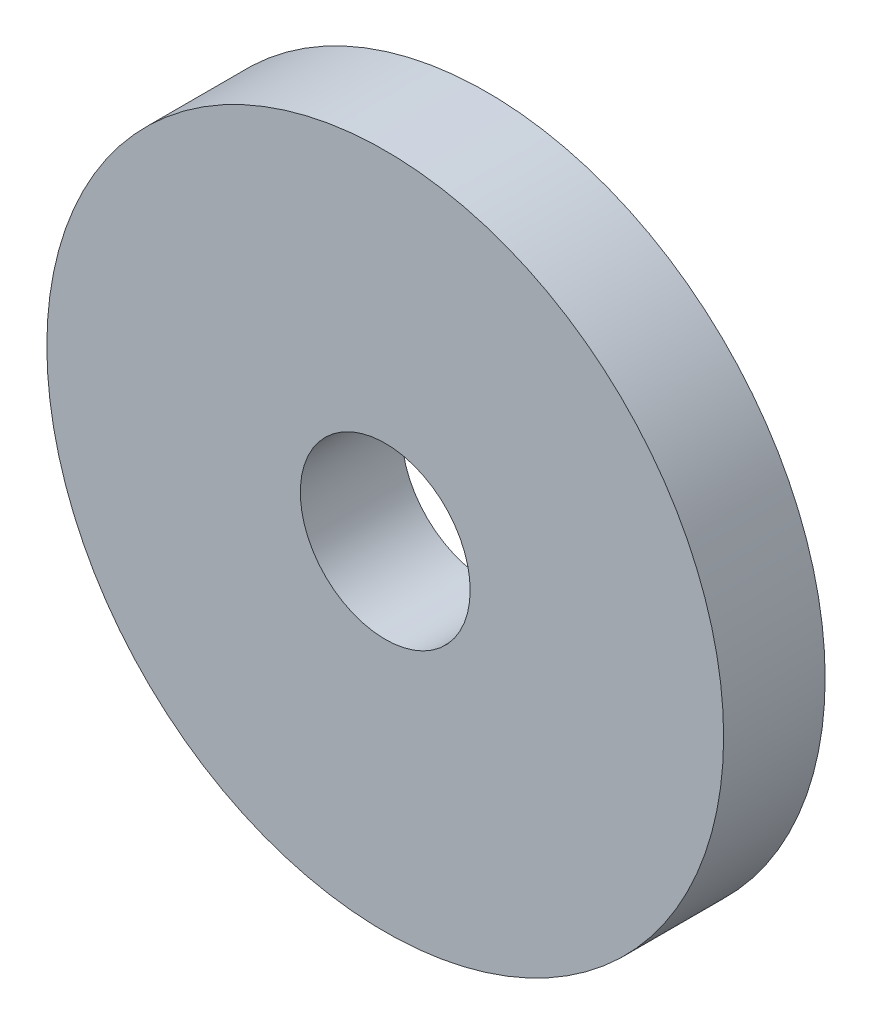
SolidWorks part; units mm, degrees
ref_plane "Front Plane" through (0, 0, 0) normal (0, 0, 1) x (1, 0, 0)
ref_plane "Top Plane" through (0, 0, 0) normal (0, 1, 0) x (1, 0, 0)
ref_plane "Right Plane" through (0, 0, 0) normal (1, 0, 0) x (0, 0, -1)
sketch "Sketch1" plane through (0, 0, 0) normal (0, 0, 1) x (1, 0, 0)
  circle A0 centre (0, 0) radius 10
  circle A1 centre (0, 0) radius 2.51
  dimension "D1" = 20
  dimension "D2" = 5.02
extrude "Boss-Extrude1" add sketch "Sketch1" along normal blind 3
